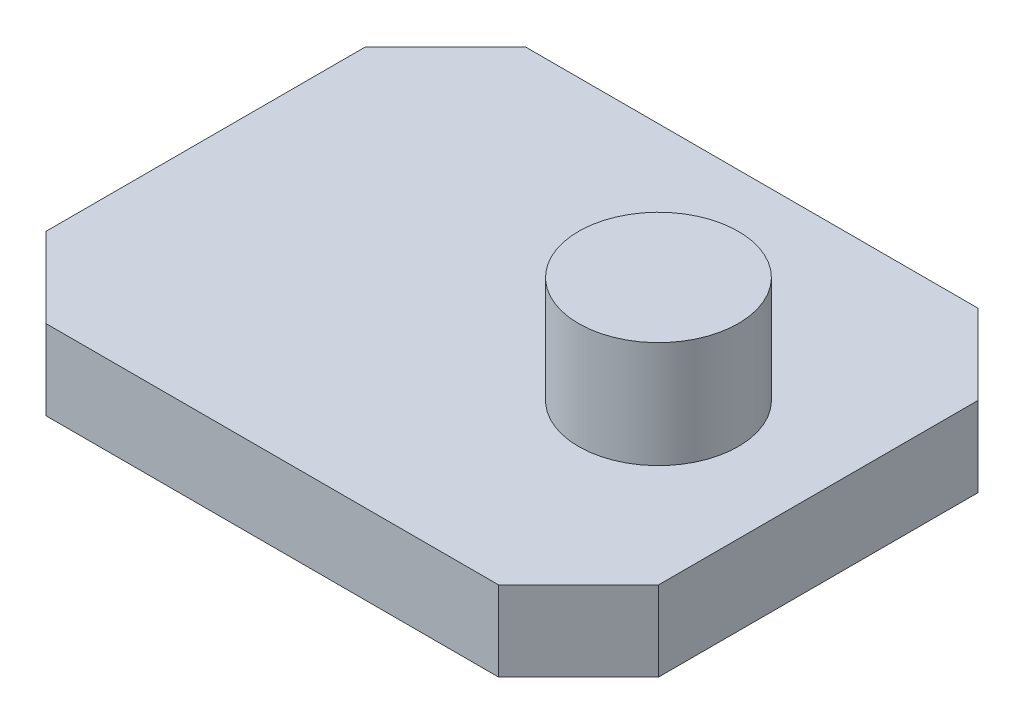
SolidWorks part; units mm, degrees
ref_plane "前视基准面" through (0, 0, 0) normal (0, 0, 1) x (1, 0, 0)
ref_plane "上视基准面" through (0, 0, 0) normal (0, 1, 0) x (1, 0, 0)
ref_plane "右视基准面" through (0, 0, 0) normal (1, 0, 0) x (0, 0, -1)
sketch "草图1" plane through (0, 0, 0) normal (0, 1, 0) x (1, 0, 0)
  line L1 (-11.5, 9) -> (11.5, 9)
  line L2 (-11.5, 9) -> (-11.5, -9)
  line L3 (-11.5, -9) -> (11.5, -9)
  line L4 (11.5, 9) -> (11.5, -9)
  line L5 (-11.5, 9) -> (11.5, -9) construction
  line L6 (-11.5, -9) -> (11.5, 9) construction
  point P0 (0, 0)
  dimension "D1" = 23
  dimension "D2" = 18
extrude "凸台-拉伸1" add sketch "草图1" along normal mid plane 3
chamfer "倒角1" distance 3 angle 45 4 edges at (11.5, 0, 9) (11.5, 0, -9) (-11.5, 0, -9) (-11.5, 0, 9)
sketch "草图2" plane through (0, 1.5, 0) normal (0, 1, 0) x (1, 0, 0)
  line L0 (11.5, -6) -> (11.5, 6) construction
  circle A0 centre (5.5, 0) radius 3
  point P4 (0, 0)
  dimension "D1" = 6
  dimension "D2" = 6
extrude "凸台-拉伸2" add sketch "草图2" along normal blind 4
